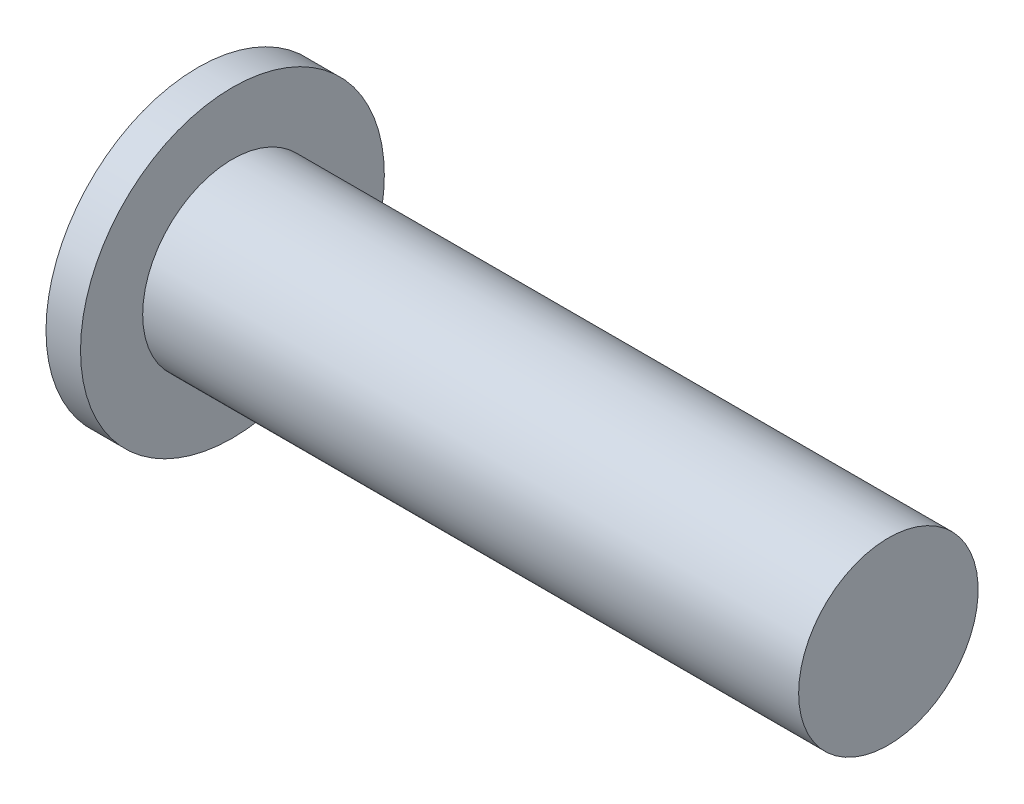
SolidWorks part; units mm, degrees
ref_plane "Front Plane" through (0, 0, 0) normal (0, 0, 1) x (1, 0, 0)
ref_plane "Top Plane" through (0, 0, 0) normal (0, 1, 0) x (1, 0, 0)
ref_plane "Right Plane" through (0, 0, 0) normal (1, 0, 0) x (0, 0, -1)
sketch "Sketch1" plane through (0, 0, 0) normal (1, 0, 0) x (0, 0, -1)
  circle A0 centre (0, 0) radius 11
  circle A1 centre (0, 0) radius 13
extrude "Boss-Extrude1" add sketch "Sketch1" along normal blind 90
sketch "Sketch2" plane through (90, 0, 0) normal (1, 0, 0) x (0, 0, -1)
  circle A0 centre (0, 0) radius 13
extrude "Boss-Extrude2" add sketch "Sketch2" along normal blind 5
sketch "Sketch3" plane through (0, 0, 0) normal (-1, 0, 0) x (0, 0, 1)
  circle A0 centre (0, 0) radius 22
  circle A1 centre (0, 0) radius 11
extrude "Boss-Extrude4" add sketch "Sketch3" along normal blind 5
